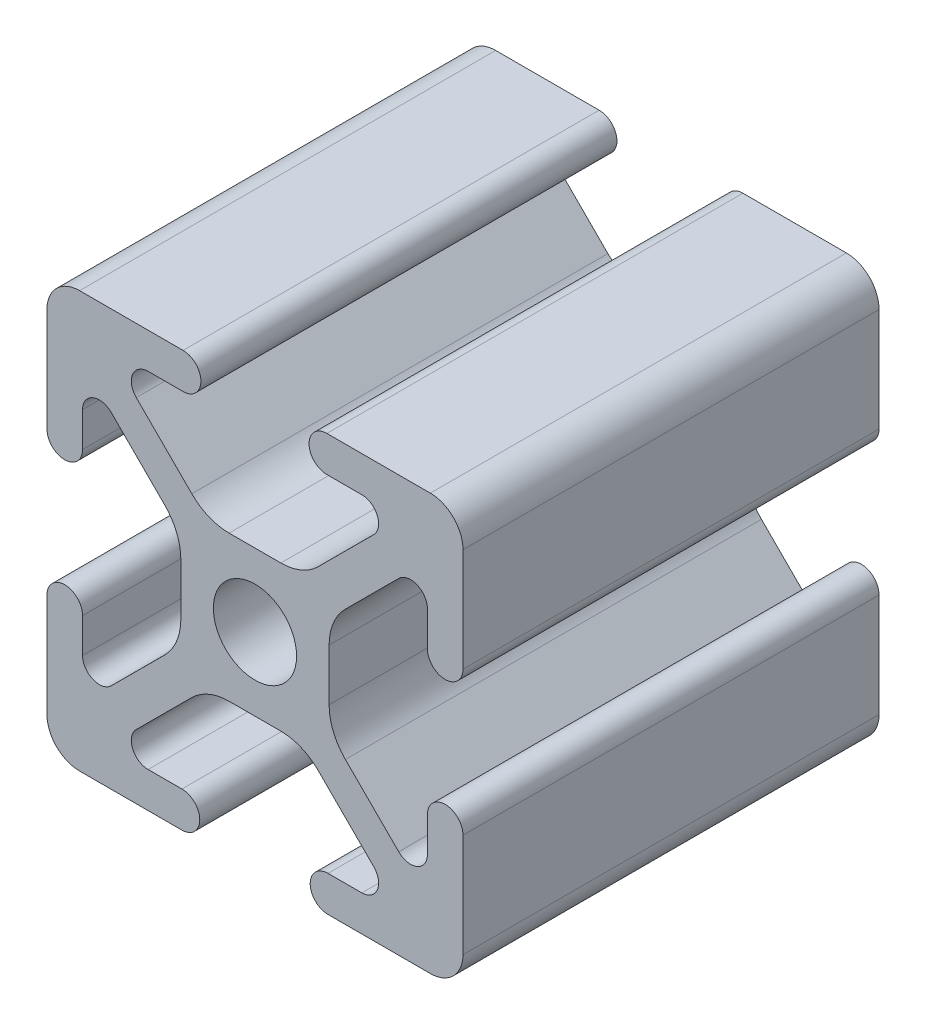
SolidWorks part; units mm, degrees
ref_plane "Front Plane" through (0, 0, 0) normal (0, 0, 1) x (1, 0, 0)
ref_plane "Top Plane" through (0, 0, 0) normal (0, 1, 0) x (1, 0, 0)
ref_plane "Right Plane" through (0, 0, 0) normal (1, 0, 0) x (0, 0, -1)
ref_plane "Plane1" through (0, 0, -4000) normal (0, 0, -1) x (-1, 0, 0)
sketch "Sketch1" plane through (0, 0, -4000) normal (0, 0, -1) x (-1, 0, 0)
  line L0 (12.5, 4.32) -> (12.5, 10.5371)
  line L1 (10.5371, 12.5) -> (4.32, 12.5)
  line L2 (4.32, 10.36) -> (6.42, 10.36)
  line L3 (7.1337, 8.6353) -> (3.7953, 5.3018)
  line L4 (1.5554, 4.375) -> (-1.5554, 4.375)
  line L5 (-3.7953, 5.3018) -> (-7.1337, 8.6353)
  line L6 (-6.42, 10.36) -> (-4.32, 10.36)
  line L7 (-4.32, 12.5) -> (-10.5371, 12.5)
  line L8 (-12.5, 10.5371) -> (-12.5, 4.32)
  line L9 (-10.36, 4.32) -> (-10.36, 6.3969)
  line L10 (-8.6363, 7.1116) -> (-5.4322, 3.9121)
  line L11 (-4.455, 1.5554) -> (-4.455, -1.5554)
  line L12 (-5.4322, -3.9121) -> (-8.6363, -7.1116)
  line L13 (-10.36, -6.3969) -> (-10.36, -4.32)
  line L14 (-12.5, -4.32) -> (-12.5, -10.5371)
  line L15 (-10.5371, -12.5) -> (-4.3879, -12.5)
  line L16 (-4.3879, -10.36) -> (-6.42, -10.36)
  line L17 (-7.1337, -8.6353) -> (-3.7953, -5.3018)
  line L18 (-1.5554, -4.375) -> (1.5554, -4.375)
  line L19 (3.7953, -5.3018) -> (7.1337, -8.6353)
  line L20 (6.42, -10.36) -> (4.3879, -10.36)
  line L21 (4.3879, -12.5) -> (10.5371, -12.5)
  line L22 (12.5, -10.5371) -> (12.5, -4.32)
  line L23 (10.36, -4.32) -> (10.36, -6.3969)
  line L24 (8.6363, -7.1116) -> (5.4322, -3.9121)
  line L25 (4.455, -1.5554) -> (4.455, 1.5554)
  line L26 (5.4322, 3.9121) -> (8.6363, 7.1116)
  line L27 (10.36, 6.3969) -> (10.36, 4.32)
  circle A0 centre (0, 0) radius 2.5
  arc A1 (12.5, 10.5371) -> (10.5371, 12.5) centre (10.5371, 10.5371) ccw
  arc A2 (4.32, 12.5) -> (4.32, 10.36) centre (4.32, 11.43) ccw
  arc A3 (6.42, 10.36) -> (7.1337, 8.6353) centre (6.42, 9.35) cw
  arc A4 (3.7953, 5.3018) -> (1.5554, 4.375) centre (1.5554, 7.545) cw
  arc A5 (-1.5554, 4.375) -> (-3.7953, 5.3018) centre (-1.5554, 7.545) cw
  arc A6 (-7.1337, 8.6353) -> (-6.42, 10.36) centre (-6.42, 9.35) cw
  arc A7 (-4.32, 10.36) -> (-4.32, 12.5) centre (-4.32, 11.43) ccw
  arc A8 (-10.5371, 12.5) -> (-12.5, 10.5371) centre (-10.5371, 10.5371) ccw
  arc A9 (-12.5, 4.32) -> (-10.36, 4.32) centre (-11.43, 4.32) ccw
  arc A10 (-10.36, 6.3969) -> (-8.6363, 7.1116) centre (-9.35, 6.3969) cw
  arc A11 (-5.4322, 3.9121) -> (-4.455, 1.5554) centre (-7.7855, 1.5554) cw
  arc A12 (-4.455, -1.5554) -> (-5.4322, -3.9121) centre (-7.7855, -1.5554) cw
  arc A13 (-8.6363, -7.1116) -> (-10.36, -6.3969) centre (-9.35, -6.3969) cw
  arc A14 (-10.36, -4.32) -> (-12.5, -4.32) centre (-11.43, -4.32) ccw
  arc A15 (-12.5, -10.5371) -> (-10.5371, -12.5) centre (-10.5371, -10.5371) ccw
  arc A16 (-4.3879, -12.5) -> (-4.3879, -10.36) centre (-4.3879, -11.43) ccw
  arc A17 (-6.42, -10.36) -> (-7.1337, -8.6353) centre (-6.42, -9.35) cw
  arc A18 (-3.7953, -5.3018) -> (-1.5554, -4.375) centre (-1.5554, -7.545) cw
  arc A19 (1.5554, -4.375) -> (3.7953, -5.3018) centre (1.5554, -7.545) cw
  arc A20 (7.1337, -8.6353) -> (6.42, -10.36) centre (6.42, -9.35) cw
  arc A21 (4.3879, -10.36) -> (4.3879, -12.5) centre (4.3879, -11.43) ccw
  arc A22 (10.5371, -12.5) -> (12.5, -10.5371) centre (10.5371, -10.5371) ccw
  arc A23 (12.5, -4.32) -> (10.36, -4.32) centre (11.43, -4.32) ccw
  arc A24 (10.36, -6.3969) -> (8.6363, -7.1116) centre (9.35, -6.3969) cw
  arc A25 (5.4322, -3.9121) -> (4.455, -1.5554) centre (7.7855, -1.5554) cw
  arc A26 (4.455, 1.5554) -> (5.4322, 3.9121) centre (7.7855, 1.5554) cw
  arc A27 (8.6363, 7.1116) -> (10.36, 6.3969) centre (9.35, 6.3969) cw
  arc A28 (10.36, 4.32) -> (12.5, 4.32) centre (11.43, 4.32) ccw
extrude "Boss-Extrude1" add sketch "Sketch1" against normal blind 25
